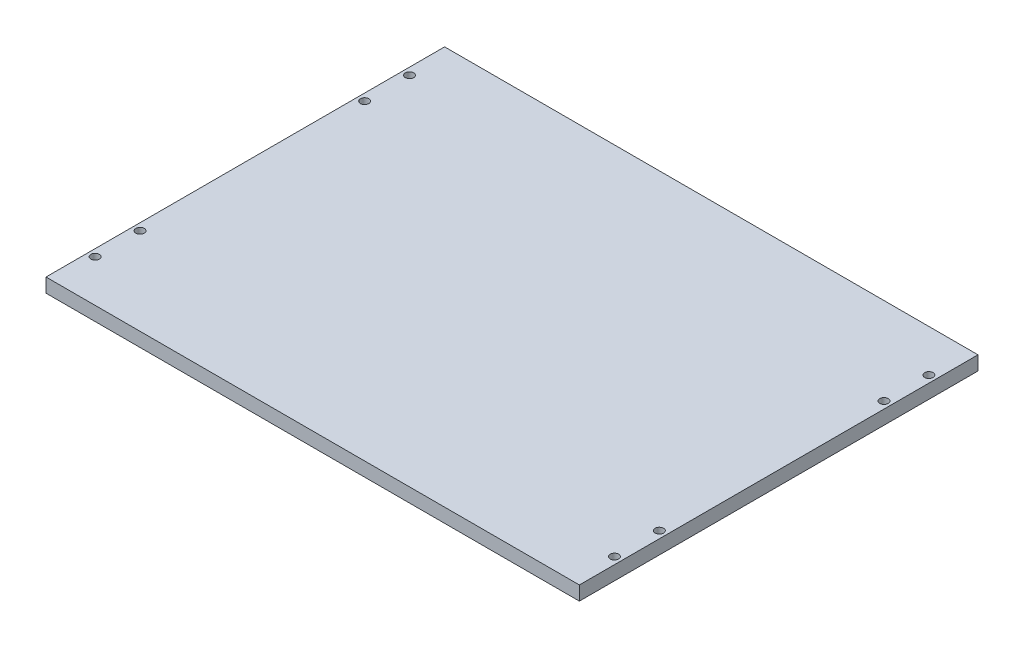
SolidWorks part; units mm, degrees
ref_plane "Front Plane" through (0, 0, 0) normal (0, 0, 1) x (1, 0, 0)
ref_plane "Top Plane" through (0, 0, 0) normal (0, 1, 0) x (1, 0, 0)
ref_plane "Right Plane" through (0, 0, 0) normal (1, 0, 0) x (0, 0, -1)
sketch "Sketch1" plane through (0, 0, 0) normal (0, 1, 0) x (1, 0, 0)
  line L1 (0, 0) -> (95, 0)
  line L2 (0, 0) -> (0, 142)
  line L3 (0, 142) -> (95, 142)
  line L4 (95, 0) -> (95, 142)
  circle A0 centre (92.5, 15) radius 1.5
  circle A2 centre (92.5, 31) radius 1.5
  circle A3 centre (92.5, 127) radius 1.5
  circle A5 centre (92.5, 111) radius 1.5
  dimension "D4" = 3
  dimension "D5" = 3
  dimension "D12" = 3
  dimension "D14" = 3
  dimension "D1" = 95
  dimension "D2" = 142
  dimension "D6" = 2.5
  dimension "D8" = 2.5
  dimension "D9" = 15
  dimension "D10" = 31
  dimension "D15" = 15
  dimension "D16" = 31
extrude "Boss-Extrude1" add sketch "Sketch1" along normal blind 5
mirror "Mirror1" about plane through (0, 5, 0) normal (1, 0, 0) of "Boss-Extrude1"
